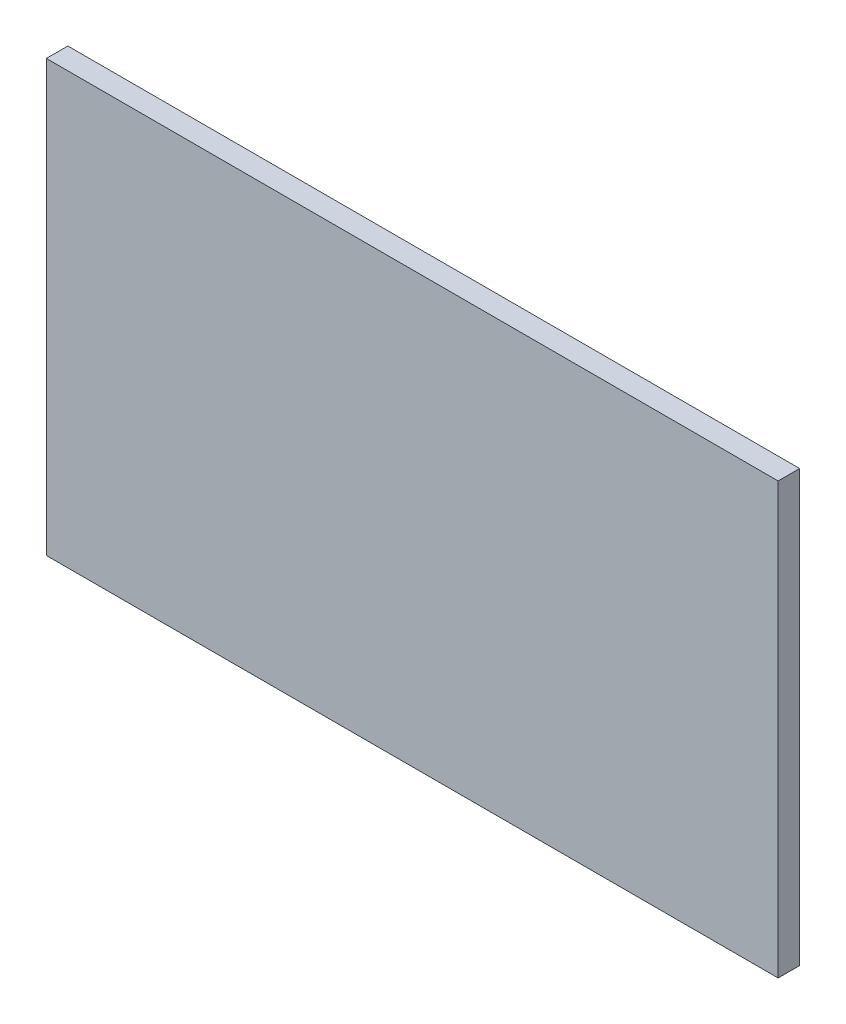
SolidWorks part; units mm, degrees
ref_plane "前视基准面" through (0, 0, 0) normal (0, 0, 1) x (1, 0, 0)
ref_plane "上视基准面" through (0, 0, 0) normal (0, 1, 0) x (1, 0, 0)
ref_plane "右视基准面" through (0, 0, 0) normal (1, 0, 0) x (0, 0, -1)
sketch "草图1" plane through (0, 0, 0) normal (0, 0, 1) x (1, 0, 0)
  line L1 (170, -100) -> (-170, -100)
  line L2 (170, -100) -> (170, 100)
  line L3 (170, 100) -> (-170, 100)
  line L4 (-170, -100) -> (-170, 100)
  line L5 (170, -100) -> (-170, 100) construction
  line L6 (170, 100) -> (-170, -100) construction
  point P0 (0, 0)
  dimension "D1" = 340
  dimension "D2" = 200
extrude "凸台-拉伸1" add sketch "草图1" along normal blind 10
